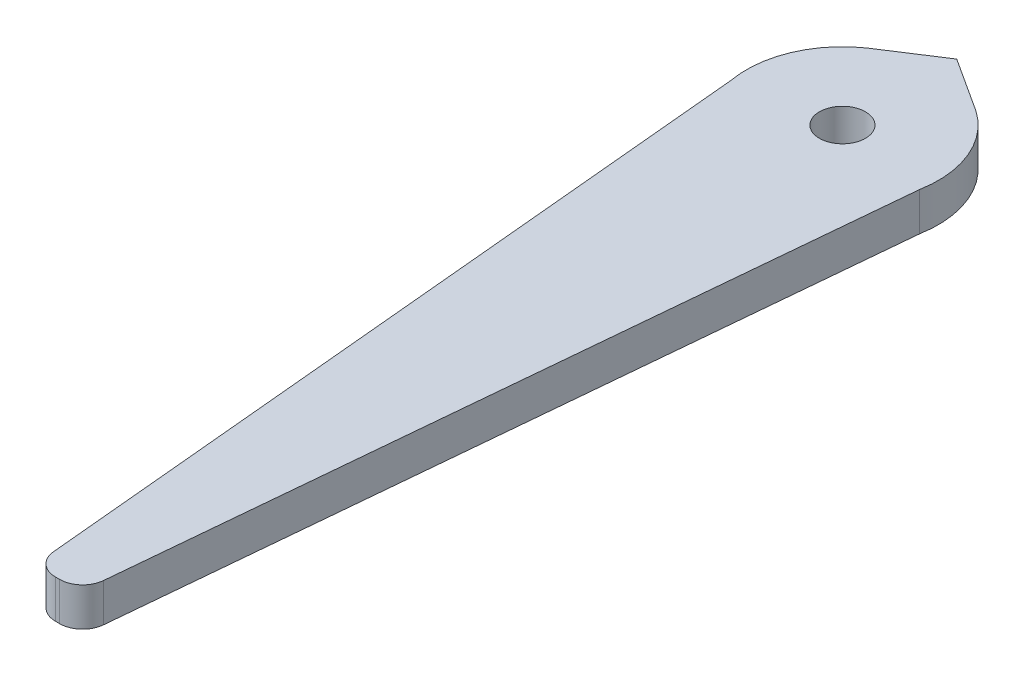
SolidWorks part; units mm, degrees
ref_plane "Alzado" through (0, 0, 0) normal (0, 0, 1) x (1, 0, 0)
ref_plane "Planta" through (0, 0, 0) normal (0, 1, 0) x (1, 0, 0)
ref_plane "Vista lateral" through (0, 0, 0) normal (1, 0, 0) x (0, 0, -1)
sketch "Croquis1" plane through (0, 0, 0) normal (0, 1, 0) x (1, 0, 0)
  line L3 (-13.3685, 198.5832) -> (11.6315, 198.5832) construction
  line L4 (-0.8685, 213.0995) -> (-0.8685, 198.5832) construction
  line L6 (-0.8685, 205.8413) -> (-11.0454, 205.8413) construction
  line L7 (-11.0454, 205.8413) -> (9.3084, 205.8413) construction
  line L8 (-0.8685, 213.0995) -> (-0.8685, 205.8413) construction
  line L9 (-0.8685, 205.8413) -> (-0.8685, 209.4704) construction
  line L10 (-0.8685, 209.4704) -> (-7.01, 209.4704) construction
  line L11 (-7.01, 209.4704) -> (5.273, 209.4704) construction
  line L12 (-7.9627, 208.875) -> (-0.8685, 213.4704)
  line L13 (-0.8685, 213.4704) -> (6.2257, 208.875)
  line L14 (-0.8685, 213.4704) -> (-0.8685, 209.4704) construction
  line L15 (-13.1669, 196.3473) -> (11.4299, 196.3473) construction
  line L16 (-0.8685, 196.3473) -> (-0.8685, 96.3473) construction
  line L17 (-3.8685, 96.3473) -> (2.1315, 96.3473)
  line L18 (-13.1669, 196.3473) -> (-3.8685, 96.3473)
  line L19 (2.1315, 96.3473) -> (11.4299, 196.3473)
  arc A1 (-7.9627, 208.875) -> (-13.1669, 196.3473) centre (-0.8685, 198.5832) ccw
  arc A2 (11.4299, 196.3473) -> (6.2257, 208.875) centre (-0.8685, 198.5832) ccw
  circle A3 centre (-0.8685, 198.5832) radius 3
  point P8 (0, 0)
  point P23 (-0.8685, 96.3473)
  dimension "D5" = 6
  dimension "D1" = 100
  dimension "D2" = 4
  dimension "D3" = 3.6291
  dimension "D6" = 6
  dimension "D7" = 25
extrude "Saliente-Extruir1" add sketch "Croquis1" along normal blind 5
fillet "Redondeo1" radius 2.99 2 edges at (-3.8685, 2.5, -96.3473) (2.1315, 2.5, -96.3473)
